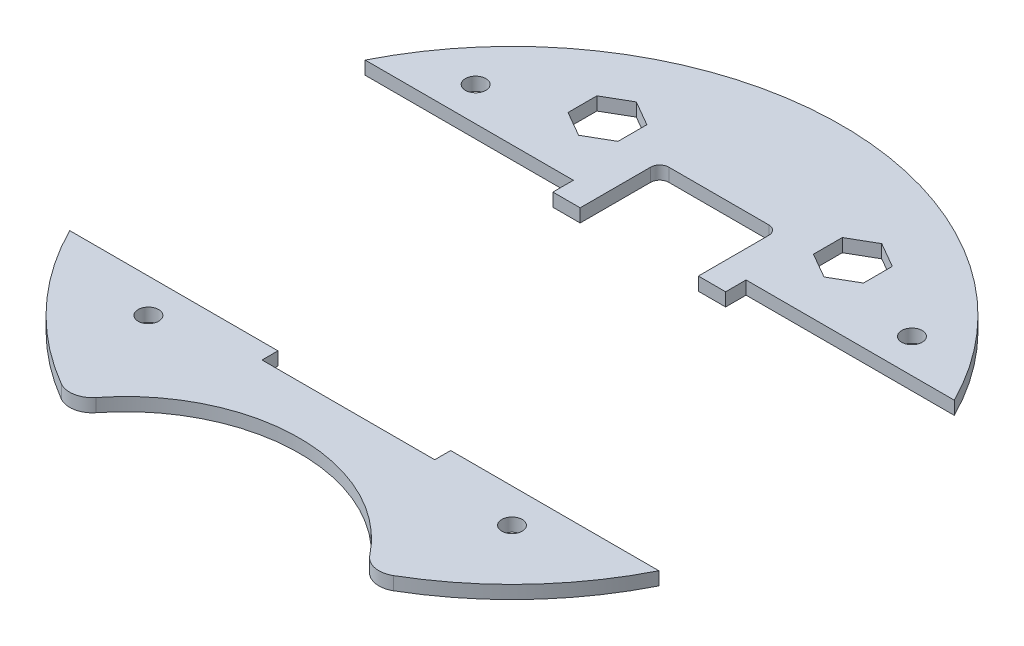
SolidWorks part; units mm, degrees
material "Acrylic (Medium-high impact)"
ref_plane "Front Plane" through (0, 0, 0) normal (0, 0, 1) x (1, 0, 0)
ref_plane "Top Plane" through (0, 0, 0) normal (0, 1, 0) x (1, 0, 0)
ref_plane "Right Plane" through (0, 0, 0) normal (1, 0, 0) x (0, 0, -1)
sketch "Sketch1" plane through (0, 0, 0) normal (0, 1, 0) x (1, 0, 0)
  line L0 (0, -85) -> (-32.4891, -64.8129) construction
  line L1 (0, -85) -> (0, 0) construction
  arc A0 (36.5434, -62.6165) -> (-36.5434, -62.6165) centre (0, 0) ccw
  arc A1 (30.0898, -61.3851) -> (-30.0898, -61.3851) centre (0, -85) ccw
  arc A2 (36.5434, -62.6165) -> (30.0898, -61.3851) centre (34.0231, -58.2982) cw
  arc A3 (-30.0898, -61.3851) -> (-36.5434, -62.6165) centre (-34.0231, -58.2982) cw
  dimension "D1" = 145
  dimension "D2" = 76.5
  dimension "D4" = 5
  dimension "D3" = 85
extrude "Boss-Extrude1" add sketch "Sketch1" along normal blind 2.9
sketch "solenoid placement" plane through (0, 2.9, 0) normal (0, 1, 0) x (1, 0, 0)
  line L4 (-19, -36) -> (19, -36)
  line L5 (-19, 28) -> (-19, -36)
  line L6 (19, 28) -> (-19, 28)
  line L7 (19, -36) -> (19, 28)
  line L8 (-19, -36) -> (19, -36)
  line L9 (-19, 28) -> (-19, -36)
  line L10 (19, 28) -> (-19, 28)
  line L11 (19, -36) -> (19, 28)
  dimension "D1" = 0
extrude "Cut-Extrude1" cut sketch "solenoid placement" against normal through all
sketch "Sketch5" plane through (0, 2.9, 0) normal (0, 1, 0) x (1, 0, 0)
  line L12 (-21.5, 51.1754) -> (-27, 54.3509)
  line L13 (-27, 54.3509) -> (-32.5, 51.1754)
  line L14 (-32.5, 51.1754) -> (-32.5, 44.8246)
  line L15 (-32.5, 44.8246) -> (-27, 41.6491)
  line L16 (-27, 41.6491) -> (-21.5, 44.8246)
  line L17 (-21.5, 44.8246) -> (-21.5, 51.1754)
  line L18 (-21.5, 51.1754) -> (-27, 54.3509)
  line L19 (-27, 54.3509) -> (-32.5, 51.1754)
  line L20 (-32.5, 51.1754) -> (-32.5, 44.8246)
  line L21 (-32.5, 44.8246) -> (-27, 41.6491)
  line L22 (-27, 41.6491) -> (-21.5, 44.8246)
  line L23 (-21.5, 44.8246) -> (-21.5, 51.1754)
  line L24 (21.5, 51.1754) -> (21.5, 44.8246)
  line L25 (21.5, 44.8246) -> (27, 41.6491)
  line L26 (27, 41.6491) -> (32.5, 44.8246)
  line L27 (32.5, 44.8246) -> (32.5, 51.1754)
  line L28 (32.5, 51.1754) -> (27, 54.3509)
  line L29 (27, 54.3509) -> (21.5, 51.1754)
  line L42 (21.5, 51.1754) -> (21.5, 44.8246)
  line L43 (21.5, 44.8246) -> (27, 41.6491)
  line L44 (27, 41.6491) -> (32.5, 44.8246)
  line L45 (32.5, 44.8246) -> (32.5, 51.1754)
  line L46 (32.5, 51.1754) -> (27, 54.3509)
  line L47 (27, 54.3509) -> (21.5, 51.1754)
  dimension "D1" = 0
  dimension "D2" = 0
extrude "Cut-Extrude5" cut sketch "Sketch5" against normal through all
sketch "Sketch6" plane through (0, 2.9, 0) normal (0, 1, 0) x (1, 0, 0)
  circle A0 centre (48, 40) radius 2.25
  circle A1 centre (40, -40) radius 2.4
  circle A2 centre (40, -40) radius 2.4 construction
  circle A3 centre (-40, -40) radius 2.4
  circle A4 centre (-40, -40) radius 2.4 construction
  circle A5 centre (48, 40) radius 2.4
  circle A6 centre (48, 40) radius 2.4 construction
  circle A7 centre (-48, 40) radius 2.4
  circle A8 centre (-48, 40) radius 2.4 construction
  circle A9 centre (-48, 40) radius 2.25
  circle A10 centre (40, -40) radius 2.25
  circle A11 centre (-40, -40) radius 2.25
  dimension "D5" = 4.5
  dimension "D2" = 0
  dimension "D3" = 0
extrude "Cut-Extrude6" cut sketch "Sketch6" against normal through all
sketch "Sketch3" plane through (0, 2.9, 0) normal (0, 1, 0) x (1, 0, 0)
  line L0 (-19, 28) -> (-19, 32.5)
  line L1 (72.5, -32.5) -> (-72.5, -32.5)
  line L2 (72.5, -32.5) -> (72.5, 32.5)
  line L3 (72.5, 32.5) -> (19, 32.5)
  line L4 (-72.5, -32.5) -> (-72.5, 32.5)
  line L5 (72.5, -32.5) -> (-72.5, 32.5) construction
  line L6 (72.5, 32.5) -> (-72.5, -32.5) construction
  line L7 (-19, 28) -> (19, 28)
  line L8 (19, 28) -> (19, 32.5)
  line L9 (-19, 32.5) -> (-72.5, 32.5)
  line L10 (-19, 28) -> (-19, -36) construction
  arc A0 (36.5434, -62.6165) -> (-36.5434, -62.6165) centre (0, 0) ccw construction
  point P0 (0, 0)
  dimension "D1" = 65
extrude "Cut-Extrude3" cut sketch "Sketch3" against normal through all
sketch "Sketch7" plane through (0, 2.9, 0) normal (0, 1, 0) x (1, 0, 0)
  line L8 (13, 28) -> (13, 43.5)
  line L9 (-13, 28) -> (13, 28)
  line L10 (-13, 43.5) -> (-13, 28)
  line L11 (11, 45.5) -> (-11, 45.5)
  line L28 (13, 28) -> (13, 43.5)
  line L29 (-13, 28) -> (13, 28)
  line L30 (-13, 43.5) -> (-13, 28)
  line L31 (11, 45.5) -> (-11, 45.5)
  arc A4 (-11, 45.5) -> (-13, 43.5) centre (-11, 43.5) ccw
  arc A5 (13, 43.5) -> (11, 45.5) centre (11, 43.5) ccw
  arc A14 (-11, 45.5) -> (-13, 43.5) centre (-11, 43.5) ccw
  arc A15 (13, 43.5) -> (11, 45.5) centre (11, 43.5) ccw
  dimension "D1" = 0
extrude "Cut-Extrude7" cut sketch "Sketch7" against normal through all
equation "\"smallPulleyTeeth\"= 15"
equation "\"largePulleyTeeth\"= 30"
equation "\"eighthThick\"= 2.9mm"
equation "\"sixteenthThick\" = 1.7mm"
equation "\"quarterThick\"=6.0mm"
equation "\"OD\" = 145mm"
equation "\"puckAngle\" = 60.5deg"
equation "\"D1@Sketch1\"=\"OD\""
equation "\"puckDiam\" = 76.5mm"
equation "\"D2@Sketch1\"=\"puckDiam\""
equation "\"D1@Boss-Extrude1\"=\"eighthThick\""
equation "\"axlePress\" = 5.9mm"
equation "\"press\" = 0.2mm"
equation "\"wheelClear\" = 0.3mm"
equation "\"10-32clear\" = 4.8mm"
equation "\"6-32clear\" = 3.3mm"
equation "\"8-32clear\" = 4.0mm"
equation "\"wheelHeight\" = 22mm"
equation "\"wheelWell\" = 65mm"
equation "\"D1@Sketch3\"=\"wheelWell\""
equation "\"puckDist\" = 85mm"
equation "\"scoopFillet\" = 5mm"
equation "\"4-40clear\" = 3.0mm"
equation "\"D3@Sketch1\"=\"puckDist\""
equation "\"D4@Sketch1\"=\"scoopFillet\""
equation "\"10-32tap\" = 4.5mm"
equation "\"D5@Sketch6\"=\"10-32tap\""
